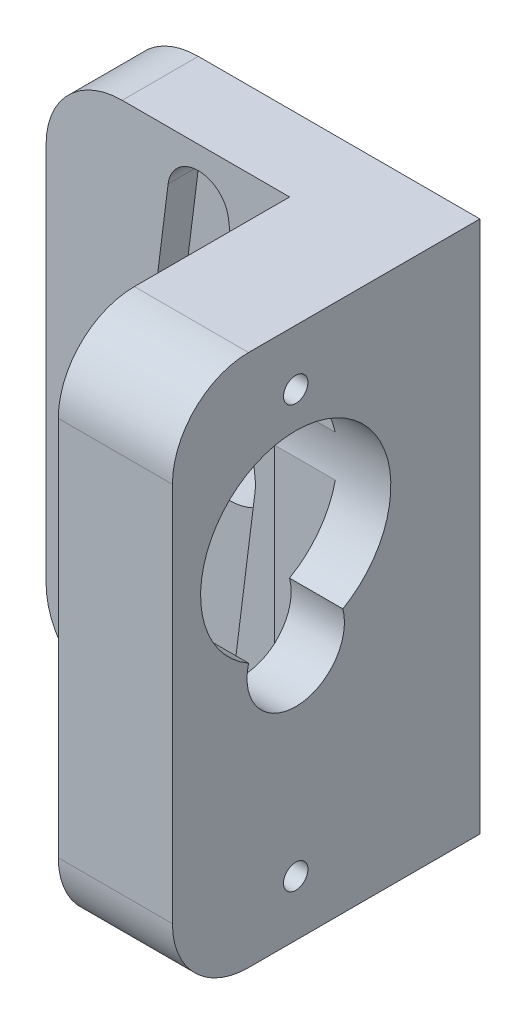
SolidWorks part; units mm, degrees
ref_plane "Front Plane" through (0, 0, 0) normal (0, 0, 1) x (1, 0, 0)
ref_plane "Top Plane" through (0, 0, 0) normal (0, 1, 0) x (1, 0, 0)
ref_plane "Right Plane" through (0, 0, 0) normal (1, 0, 0) x (0, 0, -1)
sketch "Sketch1" plane through (0, 0, 0) normal (0, 0, 1) x (1, 0, 0)
  line L0 (0, 0) -> (0, 14) construction
  line L1 (0, 0) -> (0, -14) construction
  line L2 (-3.7206, 0.4687) -> (-1.9843, 14.25) construction
  line L3 (10, -17.5) -> (-5, -17.5)
  line L4 (10, -17.5) -> (10, 17.5)
  line L5 (10, 17.5) -> (-5, 17.5)
  line L6 (-10, -12.5) -> (-10, 12.5)
  line L7 (10, -17.5) -> (-10, 17.5) construction
  line L8 (10, 17.5) -> (-10, -17.5) construction
  line L9 (-3.7206, -0.4687) -> (-1.9843, -14.25) construction
  line L10 (1.9843, -14.25) -> (3.7206, -0.4687) construction
  line L11 (1.9843, 14.25) -> (3.7206, 0.4687) construction
  arc A0 (-3.7206, 0.4687) -> (-3.7206, -0.4687) centre (0, 0) ccw construction
  arc A1 (1.9843, 14.25) -> (-1.9843, 14.25) centre (0, 14) ccw construction
  arc A2 (-1.9843, -14.25) -> (1.9843, -14.25) centre (0, -14) ccw construction
  arc A3 (-5, -17.5) -> (-10, -12.5) centre (-5, -12.5) cw
  arc A4 (-5, 17.5) -> (-10, 12.5) centre (-5, 12.5) ccw
  arc A5 (3.7206, -0.4687) -> (3.7206, 0.4687) centre (0, 0) ccw construction
  circle A6 centre (0, 0) radius 3.75
  dimension "D1" = 5
  dimension "D3" = 2
  dimension "D4" = 3.75
  dimension "D5" = 2
  dimension "D7" = 7.5
  dimension "D2" = 14
  dimension "D6" = 14
  dimension "D8" = 35
  dimension "D9" = 20
extrude "Boss-Extrude1" add sketch "Sketch1" against normal blind 5
sketch "Sketch3" plane through (0, 0, 0) normal (0, 0, 1) x (1, 0, 0)
  line L0 (0, 0) -> (-8.7328, 0) construction
  line L1 (0, 0) -> (0, 14) construction
  line L2 (0, 0) -> (6.3077, 0) construction
  line L3 (0, 0) -> (0, -14) construction
  line L4 (-1.9843, 14.25) -> (-3.7206, 0.4688)
  line L5 (-3.7206, -0.4688) -> (-1.9843, -14.25)
  line L6 (1.9843, 14.25) -> (3.7206, 0.4688)
  line L7 (1.9843, -14.25) -> (3.7206, -0.4687)
  arc A0 (1.9843, 14.25) -> (-1.9843, 14.25) centre (0, 14) ccw
  arc A1 (-1.9843, -14.25) -> (1.9843, -14.25) centre (0, -14) ccw
  arc A2 (-3.7206, 0.4688) -> (-3.7206, -0.4688) centre (0, 0) ccw
  arc A3 (3.7206, -0.4687) -> (3.7206, 0.4688) centre (0, 0) ccw
  dimension "D2" = 4
  dimension "D3" = 4
  dimension "D4" = 7.5
  dimension "D1" = 14
extrude "Cut-Extrude2" cut sketch "Sketch3" against normal blind 2
sketch "Sketch5" plane through (10, 0, 0) normal (1, 0, 0) x (0, 0, -1)
  line L0 (5, -17.5) -> (0, -17.5) construction
  line L1 (5, 17.5) -> (-10.2, 17.5)
  line L2 (5, 17.5) -> (5, -17.5)
  line L3 (5, -17.5) -> (-10.2, -17.5)
  line L4 (-15.2, 12.5) -> (-15.2, -12.5)
  line L5 (-7.1, 0) -> (-15.2, 0) construction
  line L6 (-7.1, 13.85) -> (-7.1, -13.85) construction
  line L7 (-13.2, -11.6) -> (-1, -11.6) construction
  line L8 (-13.2, -11.6) -> (-13.2, 11.6) construction
  line L9 (-13.2, 11.6) -> (-1, 11.6) construction
  line L10 (-1, -11.6) -> (-1, 11.6) construction
  line L11 (-13.2, -11.6) -> (-1, 11.6) construction
  line L12 (-13.2, 11.6) -> (-1, -11.6) construction
  line L13 (0, -17.5) -> (0, 17.5) construction
  circle A0 centre (-7.1, 13.85) radius 0.8
  circle A1 centre (-7.1, -13.85) radius 0.8
  arc A2 (-15.2, -12.5) -> (-10.2, -17.5) centre (-10.2, -12.5) ccw
  arc A3 (-15.2, 12.5) -> (-10.2, 17.5) centre (-10.2, 12.5) cw
  arc A4 (-4.0066, -0.1808) -> (-10.1934, -0.1808) centre (-7.1, 5.25) ccw
  arc A5 (-10.1934, -0.1808) -> (-4.0066, -0.1808) centre (-7.1, -1) ccw
  point P7 (-7.1, 0)
  point P16 (-7.1, 0)
  dimension "D4" = 1.6
  dimension "D6" = 5
  dimension "D1" = 12.2
  dimension "D2" = 23.2
  dimension "D3" = 2
  dimension "D5" = 27.7
  dimension "D7" = 1
extrude "Boss-Extrude2" add sketch "Sketch5" against normal blind 4 and the other way blind 3.5
sketch "Sketch6" plane through (6, 0, 0) normal (-1, 0, 0) x (0, 0, 1)
  line L0 (7.1, 13.85) -> (7.1, -13.85) construction
  line L2 (1, -11.6) -> (13.2, -11.6)
  line L3 (1, -11.6) -> (1, 11.6)
  line L4 (1, 11.6) -> (13.2, 11.6)
  line L5 (13.2, -11.6) -> (13.2, 11.6)
  line L6 (1, -11.6) -> (13.2, 11.6) construction
  line L7 (1, 11.6) -> (13.2, -11.6) construction
  point P4 (7.1, 0)
  dimension "D1" = 23.2
  dimension "D2" = 12.2
extrude "Cut-Extrude3" cut sketch "Sketch6" against normal blind 4
sketch "Sketch7" [suppressed] plane through (13.5, 0, 0) normal (1, 0, 0) x (0, 0, -1)
  circle A0 centre (-7.1, -7.6942) radius 2.2
  dimension "D1" = 4.4
extrude "Cut-Extrude4" [suppressed] cut sketch "Sketch7" against normal blind 5.2
